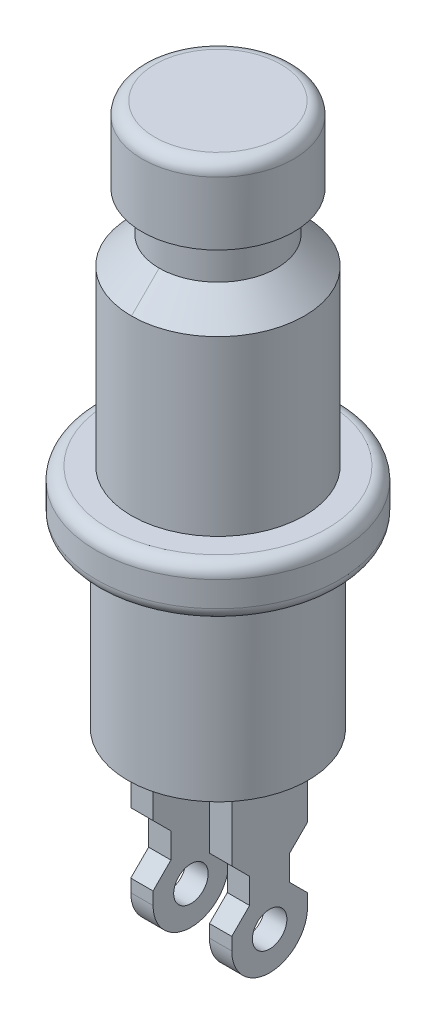
SolidWorks part; units mm, degrees
ref_plane "Front Plane" through (0, 0, 0) normal (0, 0, 1) x (1, 0, 0)
ref_plane "Top Plane" through (0, 0, 0) normal (0, 1, 0) x (1, 0, 0)
ref_plane "Right Plane" through (0, 0, 0) normal (1, 0, 0) x (0, 0, -1)
sketch "Sketch1" plane through (0, 0, 0) normal (0, 1, 0) x (1, 0, 0)
  circle A0 centre (0, 0) radius 4.815
  dimension "D1" = 9.63
extrude "Boss-Extrude1" add sketch "Sketch1" against normal blind 2
sketch "Sketch2" plane through (0, -2, 0) normal (0, -1, 0) x (1, 0, 0)
  circle A0 centre (0, 0) radius 3.575
  dimension "D1" = 7.15
extrude "Boss-Extrude2" add sketch "Sketch2" along normal blind 7
sketch "Sketch3" plane through (0, 0, 0) normal (0, 1, 0) x (1, 0, 0)
  circle A0 centre (0, 0) radius 3.425
  dimension "D1" = 6.85
extrude "Boss-Extrude3" add sketch "Sketch3" along normal blind 6.85
sketch "Sketch4" plane through (0, 6.85, 0) normal (0, 1, 0) x (1, 0, 0)
  circle A0 centre (0, 0) radius 2.33
  dimension "D1" = 4.66
extrude "Boss-Extrude4" add sketch "Sketch4" along normal blind 5
sketch "Sketch5" plane through (0, 0, 0) normal (0, 0, 1) x (1, 0, 0)
  line L0 (-3.425, 6.85) -> (-2.33, 7.945)
  line L1 (-2.33, 11.85) -> (-2.33, 6.85) construction
  line L2 (-2.33, 7.945) -> (-2.33, 6.85)
  line L3 (-2.33, 6.85) -> (-3.425, 6.85)
sweep "Sweep1" add profiles "Sketch5" path edge at (0, 6.85, 2.33)
sketch "Sketch6" plane through (0, 11.85, 0) normal (0, 1, 0) x (1, 0, 0)
  circle A0 centre (0, 0) radius 3
  dimension "D1" = 6
extrude "Boss-Extrude5" add sketch "Sketch6" along normal blind 0.67
sketch "Sketch7" plane through (0, 11.85, 0) normal (0, -1, 0) x (1, 0, 0)
  circle A0 centre (0, 0) radius 2.4444
  circle A1 centre (0, 0) radius 3
extrude "Boss-Extrude6" add sketch "Sketch7" along normal blind 2.33
sketch "Sketch8" plane through (0, 0, 0) normal (1, 0, 0) x (0, 0, -1)
  line L0 (-1.453, -9) -> (1.547, -9)
  line L1 (-3.575, -9) -> (3.575, -9) construction
  line L2 (-1.453, -9) -> (-1.453, -12)
  line L3 (1.547, -9) -> (1.547, -12)
  line L4 (-1.453, -12) -> (-0.7459, -12.7071)
  line L5 (1.547, -12) -> (0.8399, -12.7071)
  line L6 (-0.7459, -12.7071) -> (-0.7459, -13.7071)
  line L7 (0.8399, -12.7071) -> (0.8399, -13.7071)
  line L8 (-0.7459, -13.7071) -> (-1.453, -14.4142)
  line L9 (0.8399, -13.7071) -> (1.547, -14.4142)
  line L10 (-1.453, -14.4142) -> (-1.453, -14.9142)
  line L11 (1.547, -14.4142) -> (1.547, -14.9142)
  arc A0 (-1.453, -14.9142) -> (1.547, -14.9142) centre (0.047, -14.9142) ccw
  circle A1 centre (0.047, -14.9142) radius 0.683
  point P5 (0.047, -9)
  dimension "D1" = 3
  dimension "D2" = 3
  dimension "D3" = 135
  dimension "D4" = 1
  dimension "D5" = 0.5
extrude "Boss-Extrude7" add sketch "Sketch8" along normal mid plane 4
sketch "Sketch9" plane through (0, -9, 0) normal (0, -1, 0) x (1, 0, 0)
  line L0 (0, 3.575) -> (0, -3.575) construction
  line L2 (-1.1169, -3.3961) -> (1.1169, -3.3961)
  line L3 (-1.1169, -3.3961) -> (-1.1169, 3.3961)
  line L4 (-1.1169, 3.3961) -> (1.1169, 3.3961)
  line L5 (1.1169, -3.3961) -> (1.1169, 3.3961)
  line L6 (-1.1169, -3.3961) -> (1.1169, 3.3961) construction
  line L7 (-1.1169, 3.3961) -> (1.1169, -3.3961) construction
  circle A0 centre (0, 0) radius 3.575 construction
  circle A1 centre (0, 0) radius 3.575 construction
  point P7 (0, 0)
extrude "Cut-Extrude1" cut sketch "Sketch9" along normal through all
fillet "Fillet2" radius 0.5 2 edges at (0, 0, 4.815) (0, -2, 4.815)
fillet "Fillet3" radius 0.5 1 edges at (0, 12.52, 3)
